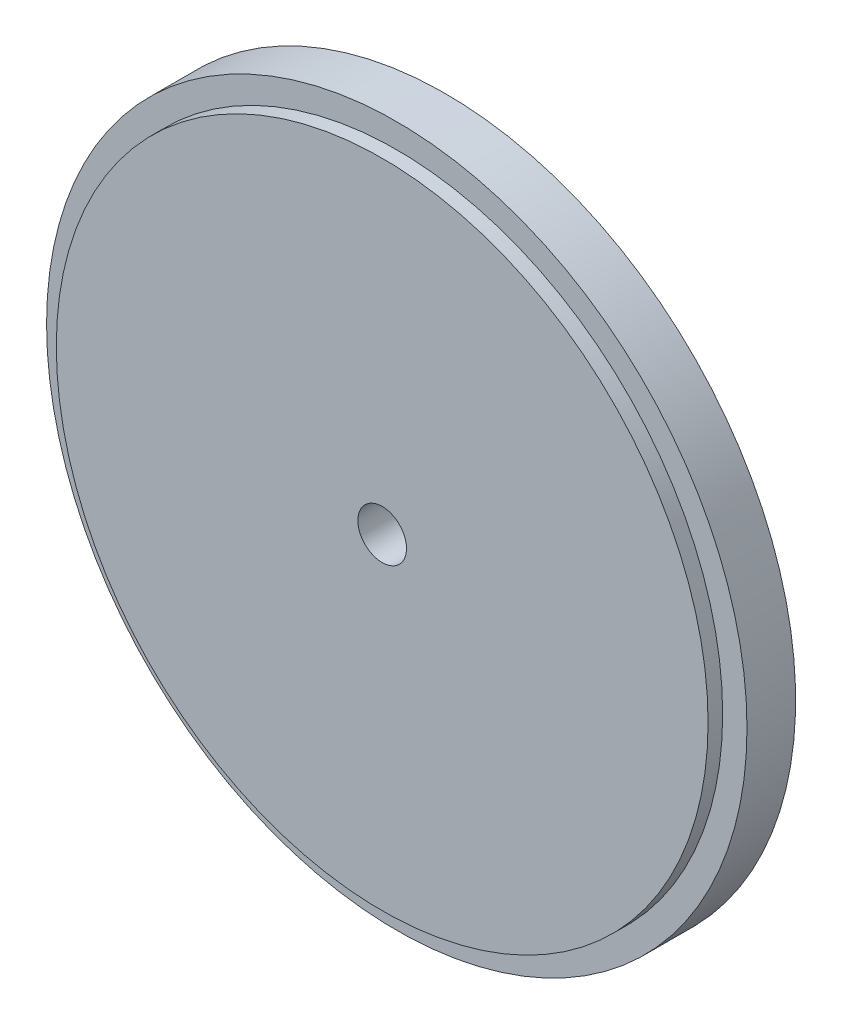
SolidWorks part; units mm, degrees
material "Liga 1060"
ref_plane "Plano frontal" through (0, 0, 0) normal (0, 0, 1) x (1, 0, 0)
ref_plane "Plano superior" through (0, 0, 0) normal (0, 1, 0) x (1, 0, 0)
ref_plane "Plano direito" through (0, 0, 0) normal (1, 0, 0) x (0, 0, -1)
sketch "Esboço1" plane through (0, 0, 0) normal (0, 0, 1) x (1, 0, 0)
  circle A0 centre (0, 0) radius 32.5
  circle A1 centre (0, 0) radius 35
extrude "Ressalto-extrusão1" add sketch "Esboço1" along normal blind 8
sketch "Esboço2" plane through (0, 0, 8) normal (0, 0, 1) x (1, 0, 0)
  circle A0 centre (0, 0) radius 32.5
extrude "Ressalto-extrusão2" add sketch "Esboço2" against normal blind 3
sketch "Esboço3" plane through (0, 0, 8) normal (0, 0, 1) x (1, 0, 0)
  circle A0 centre (0, 0) radius 2.5
extrude "Corte-extrusão1" cut sketch "Esboço3" against normal blind 3
sketch "Esboço4" plane through (0, 0, 5) normal (0, 0, -1) x (-1, 0, 0)
  circle A0 centre (0, 0) radius 37
  circle A1 centre (0, 0) radius 35
extrude "Ressalto-extrusão3" add sketch "Esboço4" against normal through all and the other way through all
sketch "Esboço5" plane through (0, 0, 0) normal (0, 1, 0) x (1, 0, 0)
  line L0 (-37, -1) -> (-37, -7)
  line L1 (-37, -4) -> (-13.2615, -4)
  line L2 (-35.2, -4) -> (-35.2, -1)
  line L3 (-35.2, -1) -> (-37, -1)
  line L4 (-35.2, -4) -> (-35.2, -7)
  line L5 (-35.2, -7) -> (-37, -7)
revolve "Corte-Revolução1" cut sketch "Esboço5" angle 360 about axis through (0, 0, 8) along (0, 0, -1)
sketch "Esboço6" plane through (0, 0, 5) normal (0, 0, -1) x (-1, 0, 0)
  circle A0 centre (0, 0) radius 12.55
  dimension "D1" = 25.1
extrude "Ressalto-extrusão4" add sketch "Esboço6" along normal blind 5
sketch "Esboço7" plane through (0, 0, 0) normal (0, 0, -1) x (-1, 0, 0)
  circle A0 centre (0, 0) radius 7.55
  dimension "D1" = 15.1
extrude "Corte-extrusão2" cut sketch "Esboço7" against normal through all both and the other way through all
sketch "Esboço8" plane through (0, 0, 8) normal (0, 0, 1) x (1, 0, 0)
  circle A0 centre (0, 0) radius 37
  circle A1 centre (0, 0) radius 32.5
  dimension "D1" = 74
extrude "Ressalto-extrusão5" add sketch "Esboço8" against normal up to surface (8 mm away) up to face at (32.5, 0, 0)
sketch "Esboço9" plane through (0, 0, 8) normal (0, 0, 1) x (1, 0, 0)
  circle A0 centre (0, 0) radius 37
  circle A1 centre (0, 0) radius 33.5
extrude "Corte-extrusão8" cut sketch "Esboço9" against normal blind 1.5
sketch "Esboço12" plane through (0, 0, 0) normal (0, 0, -1) x (-1, 0, 0)
  circle A0 centre (0, 0) radius 37
  circle A1 centre (0, 0) radius 33.5
  dimension "D1" = 74
extrude "Corte-extrusão9" cut sketch "Esboço12" against normal blind 1.5
sketch "Esboço13" plane through (0, 0, 1.5) normal (0, 0, -1) x (-1, 0, 0)
  circle A1 centre (0, 0) radius 36
  circle A2 centre (0, 0) radius 37
extrude "Corte-extrusão10" cut sketch "Esboço13" against normal blind 10
sketch "Esboço14" plane through (0, 0, 6.5) normal (0, 0, 1) x (1, 0, 0)
  circle A0 centre (0, 0) radius 37
  circle A1 centre (0, 0) radius 36
  circle A3 centre (0, 0) radius 36
  circle A6 centre (0, 0) radius 36
  circle M3 centre (0, 0) radius 36
  dimension "D1" = 0
extrude "Ressalto-extrusão6" add sketch "Esboço14" against normal up to surface (5 mm away) contours A0 M3 up to face at (-33.5, 0, 1.5)
sketch "Esboço15" plane through (0, 0, 0) normal (0, 0, -1) x (-1, 0, 0)
  circle A0 centre (0, 0) radius 12.55
extrude "Corte-extrusão11" cut sketch "Esboço15" against normal through all
sketch "Esboço16" plane through (0, 0, 5) normal (0, 0, -1) x (-1, 0, 0)
  circle A0 centre (0, 0) radius 12.55 construction
  circle A1 centre (0, 0) radius 12.55
extrude "Ressalto-extrusão7" add sketch "Esboço16" against normal through all
sketch "Esboço17" plane through (0, 0, 5) normal (0, 0, -1) x (-1, 0, 0)
  circle A0 centre (0, 0) radius 10
  dimension "D1" = 20
extrude "Ressalto-extrusão8" add sketch "Esboço17" along normal blind 16
sketch "Esboço18" plane through (0, 0, -11) normal (0, 0, -1) x (-1, 0, 0)
  circle A0 centre (0, 0) radius 2.5
  dimension "D1" = 5
extrude "Corte-extrusão12" cut sketch "Esboço18" against normal through all
sketch "Esboço19" plane through (0, 0, -11) normal (0, 0, -1) x (-1, 0, 0)
  line L0 (0, -2.5) -> (0, -4.5) construction
  line L1 (-2.975, -4.5) -> (2.975, -4.5)
  line L2 (2.975, -4.5) -> (2.975, -7.15)
  line L3 (2.975, -7.15) -> (-2.975, -7.15)
  line L4 (-2.975, -7.15) -> (-2.975, -4.5)
  line L5 (-2.5, 0) -> (2.5, 0) construction
  line L10 (-2.975, 7.15) -> (-2.975, 4.5)
  line L11 (2.975, 7.15) -> (-2.975, 7.15)
  line L12 (2.975, 4.5) -> (2.975, 7.15)
  line L13 (-2.975, 4.5) -> (2.975, 4.5)
  circle A1 centre (0, 0) radius 2.5 construction
  point P12 (0, -4.5)
  point P17 (0, 4.5)
  dimension "D1" = 2
  dimension "D2" = 5.95
  dimension "D3" = 2.65
extrude "Corte-extrusão13" cut sketch "Esboço19" against normal blind 8
sketch "Esboço21" plane through (0, 4.5, 0) normal (0, 1, 0) x (1, 0, 0)
  line L0 (0, 8.5) -> (0, 11) construction
  line L2 (-2.975, 11) -> (2.975, 11) construction
  circle A0 centre (0, 6.85) radius 1.65
  dimension "D2" = 3.3
  dimension "D1" = 2.5
extrude "Corte-extrusão14" cut sketch "Esboço21" against normal through all both and the other way through all
sketch "Esboço23" plane through (0, 0, 1.5) normal (0, 0, -1) x (-1, 0, 0)
  circle A0 centre (0, 0) radius 36
  circle A1 centre (0, 0) radius 37 construction
  circle A2 centre (0, 0) radius 37
  dimension "D1" = 72
extrude "Corte-extrusão15" cut sketch "Esboço23" against normal through all
